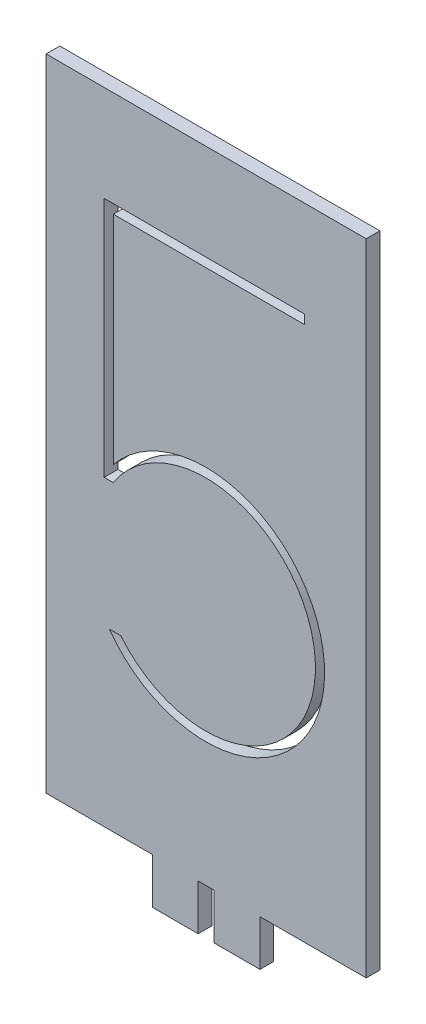
SolidWorks part; units mm, degrees
material "Glas"
ref_plane "Ebene vorne" through (0, 0, 0) normal (0, 0, 1) x (1, 0, 0)
ref_plane "Ebene oben" through (0, 0, 0) normal (0, 1, 0) x (1, 0, 0)
ref_plane "Ebene rechts" through (0, 0, 0) normal (1, 0, 0) x (0, 0, -1)
sketch "Skizze1" plane through (0, 0, 0) normal (0, 0, 1) x (1, 0, 0)
  line L1 (0, 0) -> (35, 0)
  line L2 (0, 0) -> (0, 75)
  line L3 (0, 75) -> (35, 75)
  line L4 (35, 0) -> (35, 75)
  dimension "D1" = 35
  dimension "D2" = 75
extrude "Aufsatz-Linear austragen1" add sketch "Skizze1" along normal blind 1.5
sketch "Skizze2" plane through (0, 0, 1.5) normal (0, 0, 1) x (1, 0, 0)
  line L0 (0, 0) -> (35, 0) construction
  line L1 (0, 0) -> (11.63, 0)
  line L2 (0, 0) -> (0, 5)
  line L3 (0, 5) -> (11.63, 5)
  line L4 (11.63, 0) -> (11.63, 5)
  line L5 (23.38, 5) -> (35, 5)
  line L6 (23.38, 5) -> (23.38, 0)
  line L7 (23.38, 0) -> (35, 0)
  line L8 (35, 5) -> (35, 0)
  line L9 (16.63, 0) -> (18.38, 0)
  line L10 (16.63, 0) -> (16.63, 5)
  line L11 (16.63, 5) -> (18.38, 5)
  line L12 (18.38, 0) -> (18.38, 5)
  dimension "D1" = 5
  dimension "D2" = 5
  dimension "D3" = 5
  dimension "D4" = 11.63
  dimension "D5" = 1.75
  dimension "D6" = 5
extrude "Schnitt-Linear austragen1" cut sketch "Skizze2" against normal blind 1.5
sketch "Skizze10" plane through (0, 0, 1.5) normal (0, 0, 1) x (1, 0, 0)
  line L0 (7.3504, 38.083) -> (6.3504, 38.37)
  line L9 (8.1633, 23.9989) -> (6.9026, 23.9989)
  arc A0 (6.9026, 23.9989) -> (6.3504, 38.37) centre (17.4487, 31.6003) ccw
  arc A1 (8.1633, 23.9989) -> (7.3504, 38.083) centre (17.4487, 31.6003) ccw
  dimension "D1" = 13
  dimension "D2" = 12
  dimension "D3" = 1
  dimension "D4" = 1.2606
extrude "Schnitt-Linear austragen5" cut sketch "Skizze10" against normal blind 20
sketch "Skizze11" plane through (0, 0, 1.5) normal (0, 0, 1) x (1, 0, 0)
  line L0 (35, 75) -> (0, 75) construction
  line L1 (7.3504, 38.083) -> (6.3504, 38.083)
  line L3 (7.3504, 64.5) -> (6.3504, 64.5)
  line L4 (6.3504, 38.083) -> (6.3504, 64.5)
  line L6 (7.3504, 64.5) -> (28.25, 64.5)
  line L8 (7.3504, 63.5) -> (28.25, 63.5)
  line L9 (28.25, 64.5) -> (28.25, 63.5)
  line L10 (35, 5) -> (35, 75) construction
  line L11 (7.3504, 38.083) -> (7.3504, 63.5)
  dimension "D1" = 10.5
  dimension "D2" = 0
  dimension "D3" = 1
  dimension "D4" = 6.75
  dimension "D5" = 26.417
extrude "Schnitt-Linear austragen6" cut sketch "Skizze11" against normal blind 20
